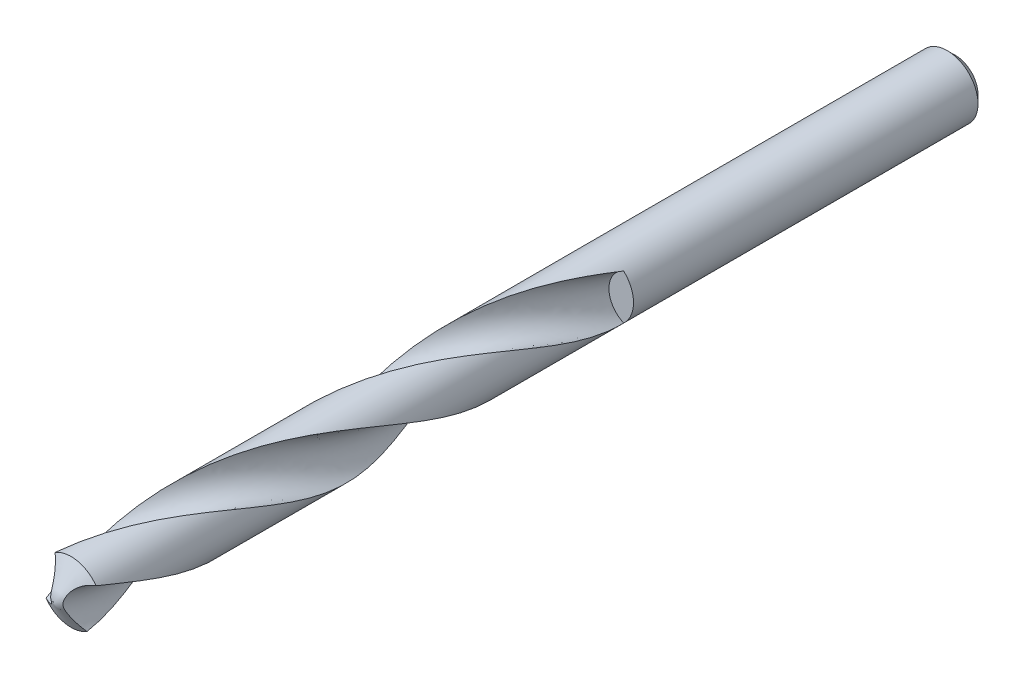
SolidWorks part; units mm, degrees
ref_plane "前基準面" through (0, 0, 0) normal (0, 0, 1) x (1, 0, 0)
ref_plane "上基準面" through (0, 0, 0) normal (0, 1, 0) x (1, 0, 0)
ref_plane "右基準面" through (0, 0, 0) normal (1, 0, 0) x (0, 0, -1)
sketch "草圖1" plane through (0, 0, 0) normal (0, 0, 1) x (1, 0, 0)
  circle A0 centre (0, 0) radius 3.75
  dimension "D1" = 7.5
extrude "填料-伸長1" add sketch "草圖1" along normal blind 110
sketch "草圖2" plane through (0, 0, 110) normal (0, 0, 1) x (1, 0, 0)
  circle A1 centre (0, 0) radius 3.75
  circle A2 centre (0, 0) radius 3.75
  dimension "D1" = 0
curve "螺旋曲線/渦捲線1" pitch 67 height 67 turns 1
sketch "草圖3" plane through (0, 0, 0) normal (0, 1, 0) x (1, 0, 0)
  arc A0 (-3.75, -43) -> (-11.7007, -30.8699) centre (-16.9786, -43) ccw
  spline S0 degree 3 poles (1986.4862, 13.307) (245.3529, -259.7569) (-18.4695, -180.6829) (-2.7207, -101.6251) (-1.4724, -97.4375) (0, -93.25) (1.4724, -89.0625) (2.7207, -84.875) (3.5547, -80.6875) (3.8476, -76.5) (3.5547, -72.3125) (2.7207, -68.125) (1.4724, -63.9375) (0, -59.75) (-1.4724, -55.5625) (-2.7207, -51.3749) (-18.4694, 27.6827) (245.3513, 106.7564) (1986.4694, -166.3044) knots -3.352891 -3.352891 -3.352891 -3.352891 0.0625 0.125 0.1875 0.25 0.3125 0.375 0.4375 0.5 0.5625 0.625 0.6875 0.75 0.8125 0.875 0.9375 4.35288 4.35288 4.35288 4.35288 only from (-3.75, -110) to (-3.75, -43) construction
  spline S1 degree 3 poles (-3.75, -110) (-3.75, -108.6051) (-3.5547, -105.812) (-2.7207, -101.6251) (-1.4724, -97.4375) (0, -93.25) (1.4724, -89.0625) (2.7207, -84.875) (3.5547, -80.6875) (3.8476, -76.5) (3.5547, -72.3125) (2.7207, -68.125) (1.4724, -63.9375) (0, -59.75) (-1.4724, -55.5625) (-2.7207, -51.3749) (-3.5547, -47.188) (-3.75, -44.3949) (-3.75, -43) knots 0 0 0 0 0.0625 0.125 0.1875 0.25 0.3125 0.375 0.4375 0.5 0.5625 0.625 0.6875 0.75 0.8125 0.875 0.9375 1 1 1 1
sketch "草圖4" plane through (0, 0, 110) normal (0, 0, 1) x (1, 0, 0)
  line L0 (3.75, 0) -> (-3.75, 0) construction
  circle A0 centre (-3.75, 0) radius 3
  point P4 (-6.3267, 0)
  dimension "D1" = 6
sweep "除料-掃出1" cut profiles "草圖4" path "螺旋曲線/渦捲線1"
pattern_circular "環狀複製排列1" count 2 over 360 about axis through (0, 0, 110) along (0, 0, -1) of "除料-掃出1"
sketch "草圖5" plane through (0, 0, 0) normal (0, 1, 0) x (1, 0, 0)
  line L0 (0, -110) -> (0, -86.2829) construction
  line L1 (-2.55, -110) -> (2.55, -110) construction
  line L2 (0, -110) -> (-8.7015, -104.9762)
  line L3 (-8.7015, -104.9762) -> (-8.7015, -119.1856)
  line L4 (-8.7015, -119.1856) -> (0, -119.1856)
  line L5 (0, -119.1856) -> (0, -110)
  dimension "D1" = 60
revolve "除料-旋轉1" cut sketch "草圖5" angle 360 about L0
chamfer "導角1" distance 1 angle 45 1 edges at (3.75, 0, 0)
